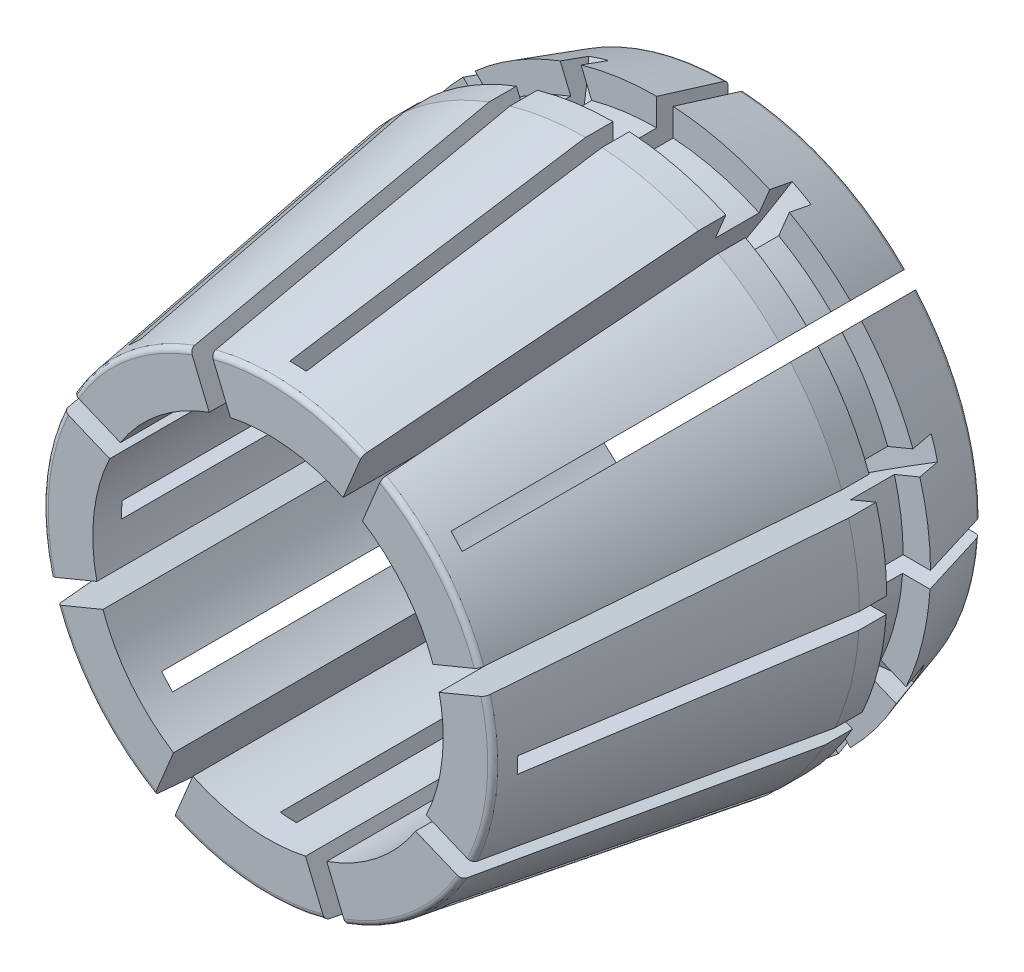
SolidWorks part; units mm, degrees
ref_plane "Front Plane" through (0, 0, 0) normal (0, 0, 1) x (1, 0, 0)
ref_plane "Top Plane" through (0, 0, 0) normal (0, 1, 0) x (1, 0, 0)
ref_plane "Right Plane" through (0, 0, 0) normal (1, 0, 0) x (0, 0, -1)
sketch "Sketch1" plane through (0, 0, 0) normal (0, 1, 0) x (1, 0, 0)
  line L0 (0, 58) -> (0, 100) construction
  line L1 (23, 100) -> (16, 100)
  line L2 (23, 100) -> (25, 93.5)
  line L3 (25, 93.5) -> (22.5, 93.5)
  line L4 (22.5, 93.5) -> (22.5, 89.5)
  line L5 (22.5, 89.5) -> (25, 89.5)
  line L6 (25, 89.5) -> (25, 87)
  line L7 (25, 87) -> (20.5, 58)
  line L8 (20.5, 58) -> (16, 58)
  line L9 (16, 100) -> (16, 58)
  dimension "D3" = 4
  dimension "D4" = 2.5
  dimension "D9" = 2.5
  dimension "D8" = 6.5
  dimension "D2" = 16
  dimension "D1" = 42
  dimension "D5" = 72.897
  dimension "D7" = 25
revolve "Revolve1" add sketch "Sketch1" angle 360 about L0
fillet "Fillet1" radius 0.5 1 edges at (23, 0, -100)
fillet "Fillet2" radius 0.5 1 edges at (20.5, 0, -58)
sketch "Sketch2" plane through (0, 0, 0) normal (1, 0, 0) x (0, 0, -1)
  line L1 (81, 0) -> (102, 0)
  line L5 (102, 0) -> (102, -21)
  arc A0 (81, 0) -> (102, -21) centre (81, -21) ccw
  dimension "D1" = 21
extrude "Cut-Extrude1" cut sketch "Sketch2" against normal blind 1.5
pattern_circular "CirPattern1" count 8 over 360 about axis through (0, 0, 0) along (0, 0, 1) of "Cut-Extrude1"
ref_plane "Plane1" through (0.3107, -0.75, 0) normal (-0.3827, 0.9239, 0) x (0.9239, 0.3827, 0)
sketch "Sketch4" plane through (0.3107, -0.75, 0) normal (-0.3827, 0.9239, 0) x (0.9239, 0.3827, 0)
  line L0 (22.6307, 100) -> (-22.6307, 100) construction
  line L1 (42.6742, 14.6516) -> (0, 14.6516)
  line L3 (0, 14.6516) -> (0, 57.3258)
  line L4 (0, 14.6516) -> (0, 57.3258)
  line L5 (22.6307, 100) -> (22.6307, 95)
  line L9 (0, 100) -> (22.6307, 100) construction
  arc A1 (42.6742, 14.6516) -> (0, 57.3258) centre (42.6742, 57.3258) ccw
  point P10 (22.6307, 100)
  dimension "D1" = 5
extrude "Cut-Extrude3" cut sketch "Sketch4" against normal blind 2
pattern_circular "CirPattern2" count 8 over 360 about axis through (0, 0, 0) along (0, 0, 1) of "Cut-Extrude3"
equation "\"colletheight\"= 42"
equation "\"slotdiam.offset\"= \"colletheight\" / 2"
equation "\"vial diam\"= 32"
equation "\"D2@Sketch1\"=\"vial diam\"/2"
equation "\"D1@Sketch1\"=\"colletheight\""
equation "\"D1@Sketch2\"=\"slotdiam.offset\""
